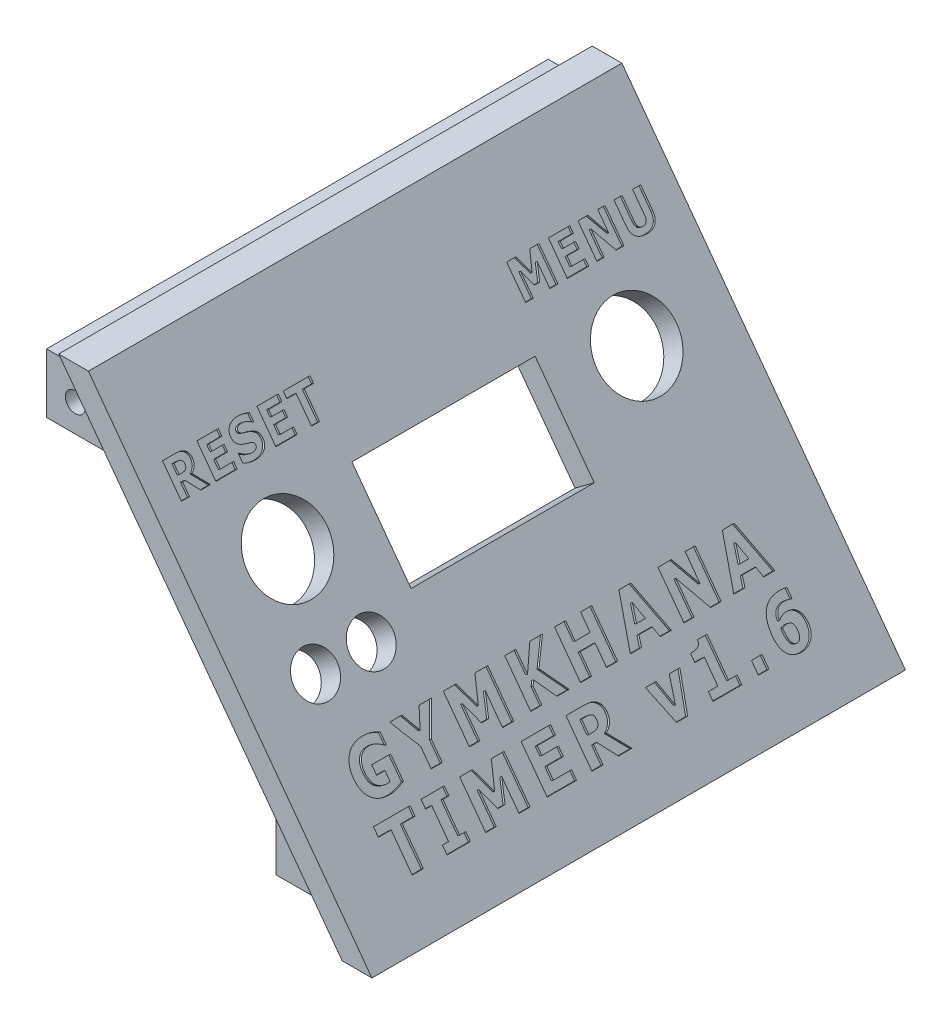
SolidWorks part; units mm, degrees
ref_plane "Płaszczyzna przednia" through (0, 0, 0) normal (0, 0, 1) x (1, 0, 0)
ref_plane "Płaszczyzna górna" through (0, 0, 0) normal (0, 1, 0) x (1, 0, 0)
ref_plane "Płaszczyzna prawa" through (0, 0, 0) normal (1, 0, 0) x (0, 0, -1)
sketch "Szkic1" plane through (0, 0, 0) normal (0, 0, 1) x (1, 0, 0)
  line L0 (51.7584, 31.5686) -> (88.06, 31.5686) construction
  line L1 (-70.2751, 31.5686) -> (55.9436, 31.5686) construction
  line L2 (84.3186, -16.6314) -> (113.2385, -16.6314) construction
  line L3 (-70.2751, -16.6314) -> (91.5515, -16.6314) construction
  line L4 (91.5515, -16.6314) -> (51.7584, 37.2339) construction
  line L5 (91.5515, -16.6314) -> (55.9436, 31.5686)
  line L6 (54.1714, 39.0164) -> (99.5742, -22.4424) construction
  line L7 (55.9436, 31.5686) -> (59.6735, 31.5686)
  line L8 (59.6735, 31.5686) -> (95.2813, -16.6314)
  line L9 (95.2813, -16.6314) -> (91.5515, -16.6314)
extrude "Dodanie-wyciągnięcie1" add sketch "Szkic1" along a picked direction on the side of the normal blind 67
sketch "Szkic2" plane through (51.2792, 37.8826, 0) normal (-0.8043, -0.5942, 0) x (0, 0, 1)
  circle A0 centre (7.5623, -20.5307) radius 3.5
  circle A1 centre (59.5623, -20.5307) radius 3.5
  circle A2 centre (7.5623, -51.5307) radius 3.5
  circle A3 centre (59.5623, -51.5307) radius 3.5
extrude "Dodanie-wyciągnięcie2" add sketch "Szkic2" along normal blind 5
sketch "Szkic3" plane through (47.2575, 34.9116, 0) normal (-0.8043, -0.5942, 0) x (0, 0, 1)
  circle A0 centre (7.5623, -20.5307) radius 1.25
  circle A1 centre (59.5623, -20.5307) radius 1.25
  circle A2 centre (7.5623, -51.5307) radius 1.25
  circle A3 centre (59.5623, -51.5307) radius 1.25
extrude "Wytnij-wyciągnięcie1" cut sketch "Szkic3" against normal blind 4
sketch "Szkic4" plane through (53.6921, 39.6652, 0) normal (0.8043, 0.5942, 0) x (0, 0, -1)
  line L3 (-45.1283, -35.2107) -> (-22.1283, -35.2107) construction
  line L4 (-45.1283, -29.4607) -> (-45.1283, -40.9607) construction
  line L7 (-22.1283, -40.9607) -> (-22.1283, -29.4607) construction
  line L8 (-45.1283, -35.2107) -> (-22.1283, -35.2107) construction
  line L9 (-45.1283, -28.9607) -> (-22.1283, -28.9607)
  line L10 (-45.1283, -28.9607) -> (-45.1283, -41.4607)
  line L11 (-45.1283, -41.4607) -> (-22.1283, -41.4607)
  line L12 (-22.1283, -28.9607) -> (-22.1283, -41.4607)
  circle A0 centre (-55.5287, -32.8472) radius 5
  circle A1 centre (-11.5959, -32.7142) radius 5
  circle A6 centre (-58.5373, -43.8207) radius 2.7
  circle A7 centre (-58.5373, -43.8207) radius 2.7
  circle A12 centre (-51.5373, -43.8207) radius 2.7
  circle A13 centre (-51.5373, -43.8207) radius 2.7
  dimension "D5" = 12.5
  dimension "D3" = 0.2
  dimension "D4" = 0.2
extrude "Wytnij-wyciągnięcie3" cut sketch "Szkic4" against normal blind 10
ref_plane "Płaszczyzna1" through (0, 0, 2) normal (0, 0, 1) x (1, 0, 0)
sketch "Szkic5" plane through (0, 0, 2) normal (0, 0, 1) x (1, 0, 0)
  line L0 (81.2325, -9.4314) -> (81.2325, -13.4314)
  line L2 (86.2325, -9.4314) -> (89.1875, -13.4314)
  line L3 (81.2325, -9.4314) -> (86.2325, -9.4314)
  line L4 (55.9436, 31.5686) -> (91.5515, -16.6314) construction
  line L5 (52.4211, 29.3686) -> (57.5689, 29.3686)
  line L8 (52.4211, 29.3686) -> (52.4211, 25.3686)
  line L9 (60.5239, 25.3686) -> (52.4211, 25.3686)
  line L10 (57.5689, 29.3686) -> (60.5239, 25.3686)
  line L11 (81.2325, -13.4314) -> (89.1875, -13.4314)
extrude "Dodanie-wyciągnięcie5" add sketch "Szkic5" along normal blind 63
sketch "Szkic7" plane through (0, 0, 67) normal (0, 0, 1) x (1, 0, 0)
  line L0 (52.4211, 25.3686) -> (60.5239, 25.3686) construction
  circle A0 centre (56.0301, 25.3686) radius 1.25
sketch "Szkic8" plane through (0, 0, 2) normal (0, 0, 1) x (1, 0, 0)
  line L0 (52.4211, 25.3686) -> (52.4211, 21.9022)
  line L1 (52.4211, 21.9022) -> (63.0847, 21.9022)
  line L2 (55.9436, 31.5686) -> (91.5515, -16.6314) construction
  line L3 (63.0847, 21.9022) -> (60.5239, 25.3686)
  line L4 (60.5239, 25.3686) -> (52.4211, 25.3686)
  line L6 (81.2325, -9.4314) -> (86.2325, -9.4314)
  line L7 (86.2325, -9.4314) -> (83.9781, -6.3798)
  line L9 (81.2325, -6.3798) -> (81.2325, -9.4314)
  line L10 (81.2325, -6.3798) -> (81.2325, -4.3462)
  line L11 (80.3513, -3.1535) -> (81.8368, -5.1643) construction
  line L12 (81.2325, -4.3462) -> (82.4758, -4.3462)
  line L13 (82.4758, -4.3462) -> (83.9781, -6.3798)
extrude "Dodanie-wyciągnięcie6" add sketch "Szkic8" along normal blind 10
ref_plane "Płaszczyzna2" through (0, 0, 65) normal (0, 0, -1) x (-1, 0, 0)
sketch "Szkic9" plane through (0, 0, 65) normal (0, 0, -1) x (-1, 0, 0)
  line L0 (-52.4211, 21.9022) -> (-52.4211, 25.3686)
  line L1 (-52.4211, 25.3686) -> (-60.5239, 25.3686)
  line L2 (-60.5239, 25.3686) -> (-63.0847, 21.9022)
  line L3 (-63.0847, 21.9022) -> (-52.4211, 21.9022)
  line L4 (-81.2325, -9.4314) -> (-81.2325, -4.3462)
  line L5 (-81.2325, -4.3462) -> (-82.4758, -4.3462)
  line L6 (-82.4758, -4.3462) -> (-86.2325, -9.4314)
  line L7 (-86.2325, -9.4314) -> (-81.2325, -9.4314)
extrude "Dodanie-wyciągnięcie7" add sketch "Szkic9" along normal blind 10
sketch "Szkic10" plane through (0, 0, 65) normal (0, 0, -1) x (-1, 0, 0)
  circle A0 centre (-56.0301, 25.3686) radius 1.25
extrude "Wytnij-wyciągnięcie7" cut sketch "Szkic10" along normal blind 6
sketch "Szkic11" plane through (0, 0, 2) normal (0, 0, 1) x (1, 0, 0)
  circle A0 centre (56.0301, 25.3686) radius 1.25
extrude "Wytnij-wyciągnięcie8" cut sketch "Szkic11" along normal blind 6
ref_plane "Płaszczyzna3" through (0, -13.6314, 0) normal (0, -1, 0) x (-1, 0, 0)
sketch "Szkic13" plane through (0, -13.6314, 0) normal (0, -1, 0) x (-1, 0, 0)
  line L1 (-69.071, -2) -> (-89.3352, -2) construction
  line L2 (-83.7325, -1.552) -> (-83.7325, -6.9991) construction
  line L3 (-89.3352, -65) -> (-69.071, -65) construction
  line L4 (-83.7325, -63.5537) -> (-83.7325, -60.4463) construction
  circle A0 centre (-83.7325, -5) radius 1.25
  circle A1 centre (-83.7325, -62) radius 1.25
  dimension "D1" = 3
  dimension "D2" = 3
extrude "Wytnij-wyciągnięcie9" cut sketch "Szkic13" against normal blind 6
sketch "Szkic16" plane through (0, 0, 65) normal (0, 0, -1) x (-1, 0, 0)
  line L0 (-82.4758, -4.3462) -> (-81.2325, -4.3462)
  line L1 (-81.2325, -4.3462) -> (-61.8414, 21.9022)
  line L2 (-52.4211, 21.9022) -> (-63.0847, 21.9022) construction
  line L3 (-61.8414, 21.9022) -> (-63.0847, 21.9022)
  line L4 (-63.0847, 21.9022) -> (-82.4758, -4.3462)
extrude "Dodanie-wyciągnięcie8" add sketch "Szkic16" along normal blind 2
sketch "Szkic17" plane through (0, 0, 2) normal (0, 0, 1) x (1, 0, 0)
  line L0 (61.8414, 21.9022) -> (63.0847, 21.9022)
  line L1 (63.0847, 21.9022) -> (82.4758, -4.3462)
  line L2 (82.4758, -4.3462) -> (81.2325, -4.3462)
  line L3 (81.2325, -4.3462) -> (61.8414, 21.9022)
extrude "Dodanie-wyciągnięcie9" add sketch "Szkic17" along normal blind 2
sketch "Szkic18" plane through (53.6921, 39.6652, 0) normal (0.8043, 0.5942, 0) x (0, 0, -1)
  text T0 "RESET            MENU" font "Tahoma" height 4
extrude "Wytnij-wyciągnięcie10" cut sketch "Szkic18" against normal blind 0.3
sketch "Szkic19" plane through (53.6921, 39.6652, 0) normal (0.8043, 0.5942, 0) x (0, 0, -1)
  text T0 "GYMKHANA" font "Tahoma" height 5.5
  text T1 "TIMER v1.6" font "Tahoma" height 5.5
extrude "Wytnij-wyciągnięcie11" cut sketch "Szkic19" against normal blind 0.3
